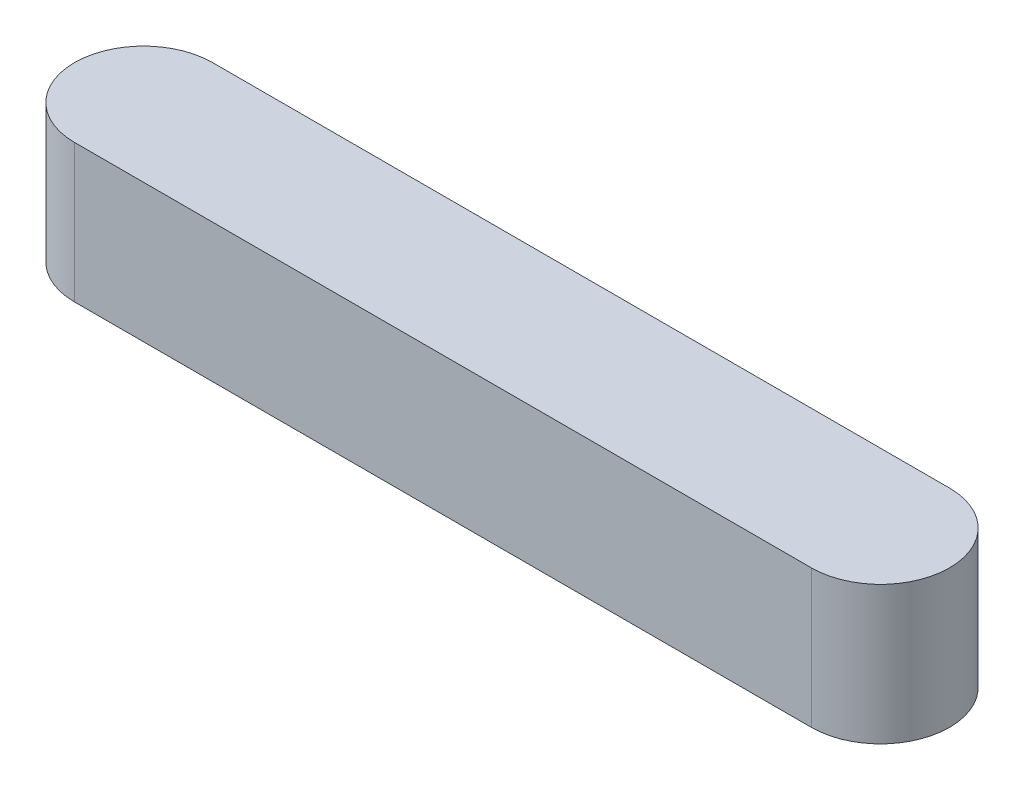
SolidWorks part; units mm, degrees
material "AISI 1020"
ref_plane "Front Plane" through (0, 0, 0) normal (0, 0, 1) x (1, 0, 0)
ref_plane "Top Plane" through (0, 0, 0) normal (0, 1, 0) x (1, 0, 0)
ref_plane "Right Plane" through (0, 0, 0) normal (1, 0, 0) x (0, 0, -1)
sketch "Sketch1" plane through (0, 0, 0) normal (0, 1, 0) x (1, 0, 0)
  line L0 (-8, 0) -> (8, 0) construction
  line L1 (-8, 1.5) -> (8, 1.5)
  line L2 (-8, -1.5) -> (8, -1.5)
  arc A0 (-8, 1.5) -> (-8, -1.5) centre (-8, 0) ccw
  arc A1 (8, -1.5) -> (8, 1.5) centre (8, 0) ccw
  point P2 (0, 0)
  dimension "D2" = 1.5
  dimension "D1" = 16
extrude "Boss-Extrude1" add sketch "Sketch1" along normal blind 3
